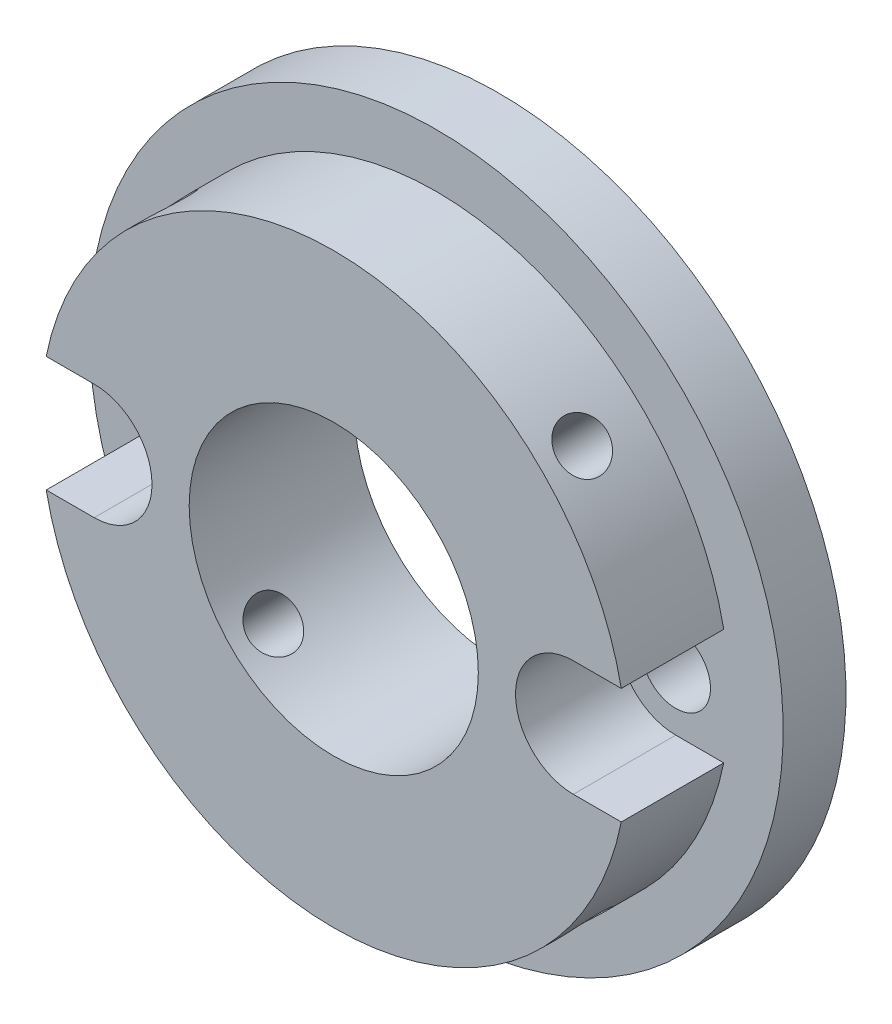
SolidWorks part; units mm, degrees
material "6061 合金"
ref_plane "正面" through (0, 0, 0) normal (0, 0, 1) x (1, 0, 0)
ref_plane "平面" through (0, 0, 0) normal (0, 1, 0) x (1, 0, 0)
ref_plane "右側面" through (0, 0, 0) normal (1, 0, 0) x (0, 0, -1)
sketch "ｽｹｯﾁ1" plane through (0, 0, 0) normal (0, 0, 1) x (1, 0, 0)
  circle A0 centre (0, 0) radius 21
  dimension "D1" = 42
extrude "ﾎﾞｽ - 押し出し1" add sketch "ｽｹｯﾁ1" along normal blind 3.8
sketch "ｽｹｯﾁ2" plane through (0, 0, 3.8) normal (0, 0, 1) x (1, 0, 0)
  circle A0 centre (0, 0) radius 17.75
  dimension "D1" = 35.5
extrude "ﾎﾞｽ - 押し出し2" add sketch "ｽｹｯﾁ2" along normal blind 6.2
sketch "ｽｹｯﾁ3" plane through (0, 0, 10) normal (0, 0, 1) x (1, 0, 0)
  line L0 (0, 17.75) -> (0, -17.75) construction
  circle A0 centre (0, 0) radius 17.75 construction
  circle A1 centre (0, 0) radius 17.75 construction
  circle A2 centre (-14.5, 0) radius 2.1
  circle A3 centre (14.5, 0) radius 2.1
  circle A4 centre (0, 0) radius 8.75
  dimension "D1" = 4.2
  dimension "D2" = 29
  dimension "D3" = 17.5
extrude "ｶｯﾄ - 押し出し1" cut sketch "ｽｹｯﾁ3" against normal through all
sketch "ｽｹｯﾁ4" plane through (0, 0, 10) normal (0, 0, 1) x (1, 0, 0)
  line L0 (0, 0) -> (12.5511, 12.5511) construction
  line L1 (-14.5, 0) -> (14.5, 0) construction
  circle A0 centre (0, 0) radius 17.75 construction
  dimension "D1" = 45
ref_plane "平面1" through (12.5511, 12.5511, 0) normal (0.7071, 0.7071, 0) x (0.7071, -0.7071, 0)
sketch "ｽｹｯﾁ5" plane through (12.5511, 12.5511, 0) normal (0.7071, 0.7071, 0) x (0.7071, -0.7071, 0)
  line L0 (0, 0) -> (0, -10) construction
  line L1 (-17.75, -10) -> (17.75, -10) construction
  circle A0 centre (0, -7.5) radius 1.5
  dimension "D1" = 2.5
  dimension "D2" = 3
extrude "ｶｯﾄ - 押し出し2" cut sketch "ｽｹｯﾁ5" against normal up to next
ref_axis "軸1" through (0, 0, 10) along (0, 0, -1)
pattern_circular "円形ﾊﾟﾀｰﾝ1" count 4 over 360 about axis through (0, 0, 10) along (0, 0, -1) of "ｶｯﾄ - 押し出し2"
sketch "ｽｹｯﾁ6" plane through (0, 0, 10) normal (0, 0, 1) x (1, 0, 0)
  line L0 (-14.5, 0) -> (-17.75, 0) construction
  line L1 (-14.5, -3.5) -> (-17.75, -3.5)
  line L2 (-14.5, 3.5) -> (-17.75, 3.5)
  line L3 (0, 0) -> (0, 21) construction
  line L4 (14.5, 0) -> (17.75, 0) construction
  line L5 (14.5, -3.5) -> (17.75, -3.5)
  line L6 (14.5, 3.5) -> (17.75, 3.5)
  circle A0 centre (0, 0) radius 17.75 construction
  circle A1 centre (0, 0) radius 17.75 construction
  arc A2 (-14.5, -3.5) -> (-14.5, 3.5) centre (-14.5, 0) ccw
  arc A3 (-17.75, 3.5) -> (-17.75, -3.5) centre (-17.75, 0) ccw
  circle A4 centre (0, 0) radius 21 construction
  arc A5 (14.5, -3.5) -> (14.5, 3.5) centre (14.5, 0) cw
  arc A6 (17.75, 3.5) -> (17.75, -3.5) centre (17.75, 0) cw
  point P7 (-16.125, 0)
  point P22 (16.125, 0)
  dimension "D1" = 3.5
extrude "ｶｯﾄ - 押し出し3" cut sketch "ｽｹｯﾁ6" against normal up to surface (6.2 mm away) up to face at (17.75, 0, 3.8)
